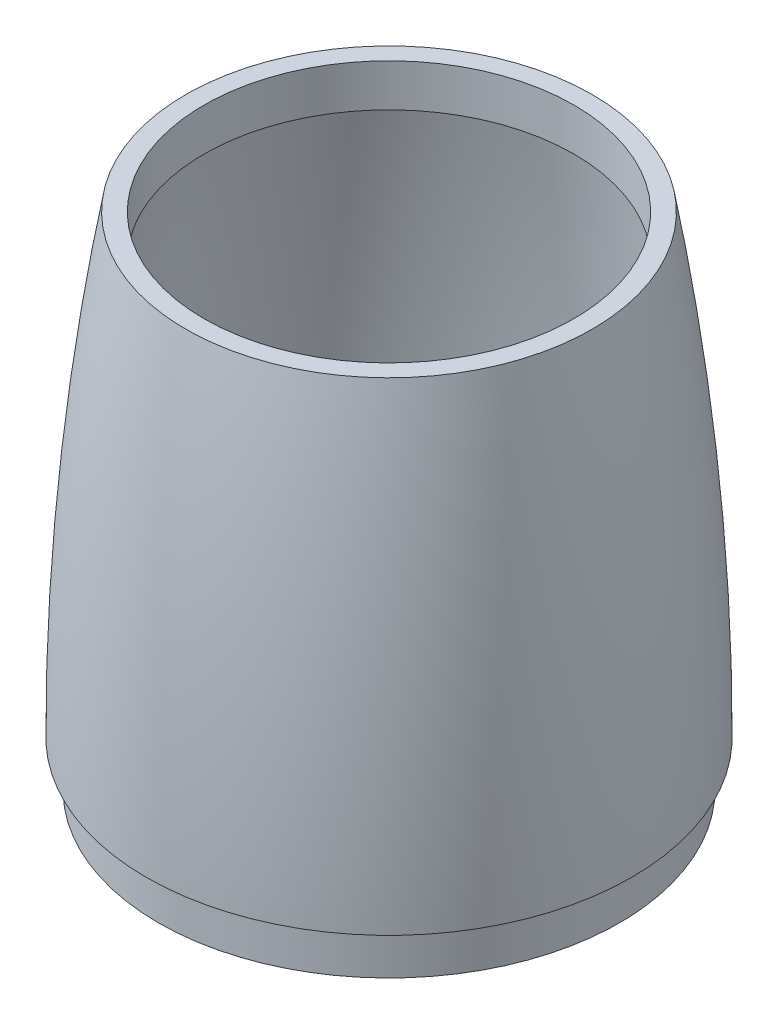
SolidWorks part; units mm, degrees
ref_plane "Front Plane" through (0, 0, 0) normal (0, 0, 1) x (1, 0, 0)
ref_plane "Top Plane" through (0, 0, 0) normal (0, 1, 0) x (1, 0, 0)
ref_plane "Right Plane" through (0, 0, 0) normal (1, 0, 0) x (0, 0, -1)
sketch "Sketch1" plane through (0, 0, 0) normal (0, 0, 1) x (1, 0, 0)
  line L0 (0, 0) -> (0, 46.1851)
  line L2 (0, 0) -> (40, 0)
  line L3 (0, 0) -> (0, 75)
  line L4 (0, 75) -> (40, 75)
  line L5 (40, 0) -> (40, 75)
  line L6 (31.6264, 68) -> (30.5, 68)
  line L7 (31.6264, 68) -> (31.6264, 75)
  line L8 (31.6264, 75) -> (30.5, 75)
  line L9 (30.5, 68) -> (30.5, 75)
  line L10 (37, 0) -> (38, 0)
  line L11 (37, 0) -> (37, -7.5)
  line L12 (37, -7.5) -> (38, -7.5)
  line L13 (38, 0) -> (38, -7.5)
  arc A0 (40, 0) -> (33.5, 75) centre (-395.9423, 0) ccw
  arc A1 (37, 0) -> (30.4543, 75) centre (-395.9423, 0) ccw
  arc A2 (37, 0) -> (30.5447, 74.4839) centre (-395.9423, 0) ccw construction
  dimension "D1" = 40
  dimension "D2" = 75
  dimension "D3" = 33.5
  dimension "D5" = 30.5
  dimension "D6" = 7
  dimension "D7" = 0
  dimension "D8" = 2
  dimension "D9" = 7.5
  dimension "D4" = 3
revolve "Revolve1" add sketch "Sketch1" angle 360 about L3
